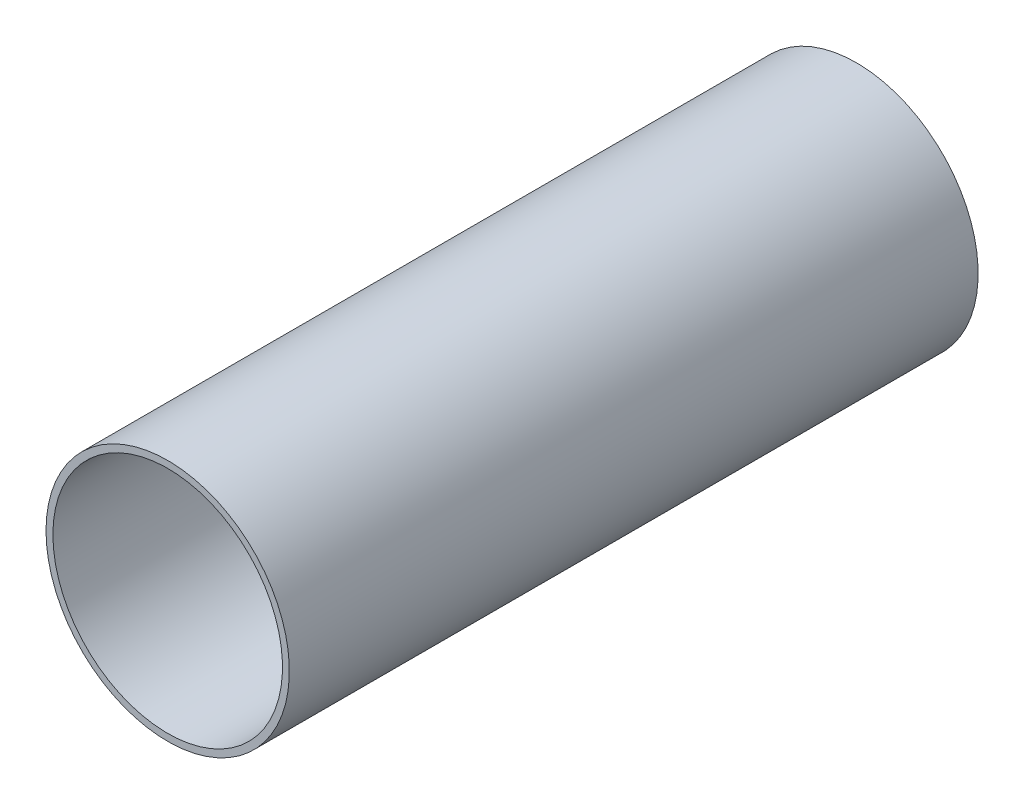
SolidWorks part; units mm, degrees
material "BUTYL"
ref_plane "Front" through (0, 0, 0) normal (0, 0, 1) x (1, 0, 0)
ref_plane "Top" through (0, 0, 0) normal (0, 1, 0) x (1, 0, 0)
ref_plane "Right" through (0, 0, 0) normal (1, 0, 0) x (0, 0, -1)
sketch "Sketch1" plane through (0, 0, 0) normal (0, 0, 1) x (1, 0, 0)
  circle A0 centre (0, 0) radius 13.462
  circle A1 centre (0, 0) radius 12.7
  dimension "D1" = 26.924
  dimension "D2" = 25.4
extrude "Boss-Extrude1" add sketch "Sketch1" along normal blind 76.2
